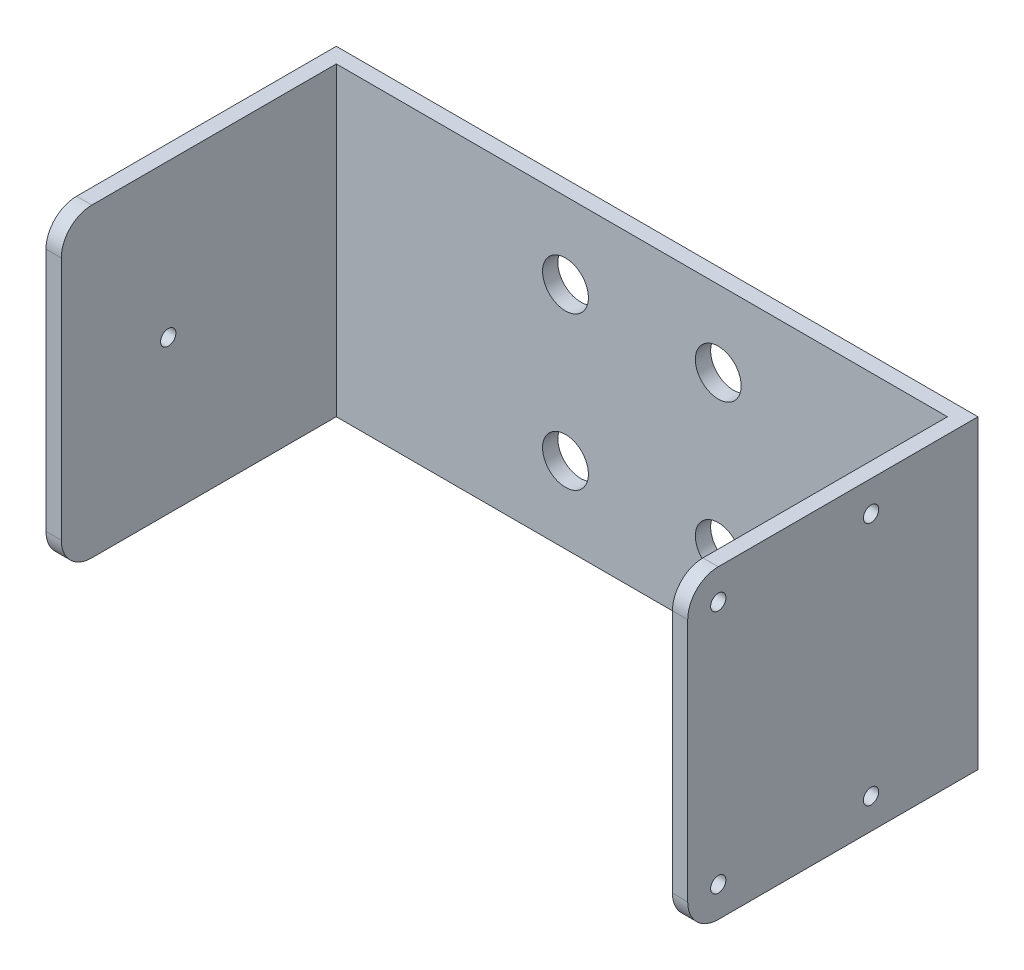
SolidWorks part; units mm, degrees
ref_plane "前视基准面" through (0, 0, 0) normal (0, 0, 1) x (1, 0, 0)
ref_plane "上视基准面" through (0, 0, 0) normal (0, 1, 0) x (1, 0, 0)
ref_plane "右视基准面" through (0, 0, 0) normal (1, 0, 0) x (0, 0, -1)
sketch "草图1" plane through (0, 0, 0) normal (0, 0, 1) x (1, 0, 0)
  line L0 (-21, 10) -> (21, -10) construction
  line L1 (-21, 10) -> (21, 10)
  line L2 (-21, 10) -> (-21, -10)
  line L3 (-21, -10) -> (21, -10)
  line L4 (21, 10) -> (21, -10)
  line L5 (-21, -10) -> (21, 10) construction
  point P5 (0, 0)
  dimension "D1" = 42
  dimension "D2" = 20
extrude "凸台-拉伸1" add sketch "草图1" along normal blind 1
sketch "草图2" plane through (0, 0, 1) normal (0, 0, 1) x (1, 0, 0)
  line L0 (-21, -10) -> (21, -10) construction
  line L1 (-21, 10) -> (-20, 10)
  line L2 (-21, 10) -> (-21, -10)
  line L3 (-21, -10) -> (-20, -10)
  line L4 (-20, 10) -> (-20, -10)
  line L6 (21, 10) -> (20, 10)
  line L7 (21, 10) -> (21, -10)
  line L8 (21, -10) -> (20, -10)
  line L9 (20, 10) -> (20, -10)
  dimension "D1" = 1
  dimension "D2" = 1
extrude "凸台-拉伸2" add sketch "草图2" along normal blind 18
sketch "草图3" plane through (21, 0, 0) normal (1, 0, 0) x (0, 0, -1)
  line L0 (-19, -10) -> (-19, 10) construction
  line L1 (-19, 10) -> (0, 10) construction
  line L3 (-19, -10) -> (0, -10) construction
  circle A0 centre (-17, 8) radius 0.5
  circle A1 centre (-7, 8) radius 0.5
  circle A2 centre (-7, -8) radius 0.5
  circle A3 centre (-17, -8) radius 0.5
  dimension "D1" = 1
  dimension "D2" = 1
  dimension "D3" = 1
  dimension "D4" = 1
  dimension "D5" = 2
  dimension "D6" = 2
  dimension "D7" = 2
  dimension "D8" = 2
  dimension "D9" = 10
  dimension "D10" = 10
extrude "切除-拉伸1" cut sketch "草图3" against normal up to next
fillet "圆角1" radius 2 2 edges at (20.5, -10, 19) (20.5, 10, 19)
fillet "圆角2" radius 2 1 edges at (-20.5, 10, 19)
fillet "圆角4" radius 2 1 edges at (-20.5, -10, 19)
sketch "草图6" plane through (-21, 0, 0) normal (-1, 0, 0) x (0, 0, 1)
  line L1 (19, 8) -> (19, -8) construction
  line L2 (0, 10) -> (0, -10) construction
  circle A0 centre (12, 0) radius 0.5
  point P7 (0, 0)
  dimension "D1" = 1
  dimension "D2" = 7
extrude "切除-拉伸2" cut sketch "草图6" against normal up to next
sketch "草图7" plane through (0, 0, 0) normal (0, 0, -1) x (-1, 0, 0)
  circle A0 centre (5, -5) radius 1.5
  circle A1 centre (-5, -5) radius 1.5
  circle A2 centre (-5, 5) radius 1.5
  circle A3 centre (5, 5) radius 1.5
  dimension "D1" = 3
  dimension "D2" = 3
  dimension "D3" = 3
  dimension "D4" = 3
  dimension "D5" = 10
  dimension "D6" = 10
  dimension "D7" = 5
  dimension "D8" = 5
extrude "切除-拉伸3" cut sketch "草图7" against normal blind 10
